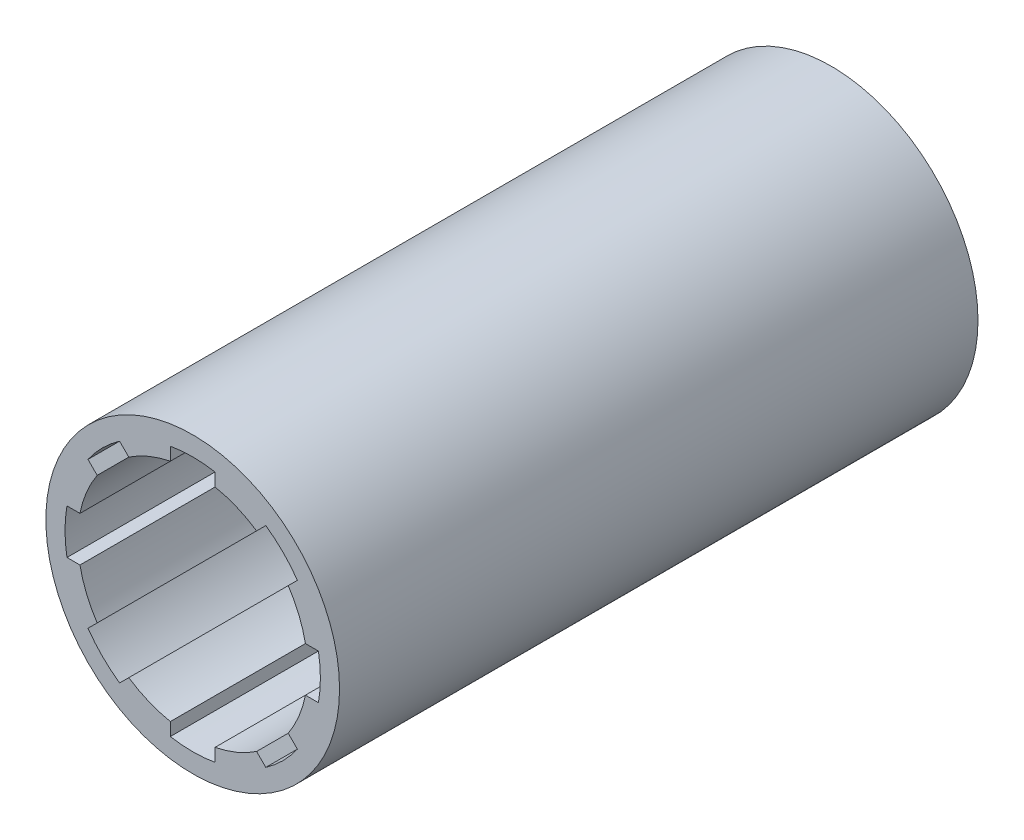
SolidWorks part; units mm, degrees
ref_plane "前视" through (0, 0, 0) normal (0, 0, 1) x (1, 0, 0)
ref_plane "上视" through (0, 0, 0) normal (0, 1, 0) x (1, 0, 0)
ref_plane "右视" through (0, 0, 0) normal (1, 0, 0) x (0, 0, -1)
sketch "草图1" plane through (0, 0, 0) normal (0, 0, 1) x (1, 0, 0)
  circle A0 centre (0, 0) radius 20
  circle A1 centre (0, 0) radius 23
extrude "凸台-拉伸1" add sketch "草图1" along normal blind 100
sketch "草图2" plane through (0, 0, 100) normal (0, 0, 1) x (1, 0, 0)
  line L0 (0, 25.9683) -> (0, -26.9652) construction
  line L1 (28.5193, 0) -> (-30.328, 0) construction
  line L2 (11.449, 16.3988) -> (10.0101, 14.9599)
  line L3 (3.5, 19.6914) -> (3.5, 17.6564)
  line L4 (-3.5, 19.6914) -> (-3.5, 17.6564)
  line L5 (16.3988, 11.449) -> (14.9599, 10.0101)
  line L6 (19.6914, 3.5) -> (17.6564, 3.5)
  line L7 (19.6914, -3.5) -> (17.6564, -3.5)
  line L8 (16.3988, -11.449) -> (14.9599, -10.0101)
  line L9 (11.449, -16.3988) -> (10.0101, -14.9599)
  line L10 (3.5, -19.6914) -> (3.5, -17.6564)
  line L11 (-3.5, -19.6914) -> (-3.5, -17.6564)
  line L12 (-11.449, -16.3988) -> (-10.0101, -14.9599)
  line L13 (-16.3988, -11.449) -> (-14.9599, -10.0101)
  line L14 (-19.6914, -3.5) -> (-17.6564, -3.5)
  line L15 (-19.6914, 3.5) -> (-17.6564, 3.5)
  line L16 (-16.3988, 11.449) -> (-14.9599, 10.0101)
  line L17 (-11.449, 16.3988) -> (-10.0101, 14.9599)
  line L18 (0, 0) -> (3.5, 17.6564) construction
  arc A0 (10.0101, 14.9599) -> (3.5, 17.6564) centre (0, 0) ccw
  arc A1 (10.0101, 14.9599) -> (3.5, 17.6564) centre (0, 0) ccw
  arc A2 (-19.6914, -3.5) -> (-16.3988, -11.449) centre (0, 0) ccw
  arc A3 (-19.6914, -3.5) -> (-16.3988, -11.449) centre (0, 0) ccw
  arc A4 (10.0101, 14.9599) -> (3.5, 17.6564) centre (0, 0) ccw
  arc A5 (-19.6914, -3.5) -> (-16.3988, -11.449) centre (0, 0) ccw
  arc A6 (10.0101, 14.9599) -> (3.5, 17.6564) centre (0, 0) ccw
  arc A7 (-19.6914, -3.5) -> (-16.3988, -11.449) centre (0, 0) ccw
  arc A8 (10.0101, 14.9599) -> (3.5, 17.6564) centre (0, 0) ccw
  arc A9 (-19.6914, -3.5) -> (-16.3988, -11.449) centre (0, 0) ccw
  arc A10 (10.0101, 14.9599) -> (3.5, 17.6564) centre (0, 0) ccw
  arc A11 (-19.6914, -3.5) -> (-16.3988, -11.449) centre (0, 0) ccw
  arc A12 (10.0101, 14.9599) -> (3.5, 17.6564) centre (0, 0) ccw
  arc A13 (-19.6914, -3.5) -> (-16.3988, -11.449) centre (0, 0) ccw
  arc A14 (10.0101, 14.9599) -> (3.5, 17.6564) centre (0, 0) ccw
  arc A15 (-19.6914, -3.5) -> (-16.3988, -11.449) centre (0, 0) ccw
  arc A16 (-3.5, 17.6564) -> (-10.0101, 14.9599) centre (0, 0) ccw
  arc A17 (-3.5, 17.6564) -> (-10.0101, 14.9599) centre (0, 0) ccw
  arc A18 (-3.5, 17.6564) -> (-10.0101, 14.9599) centre (0, 0) ccw
  arc A19 (-3.5, 17.6564) -> (-10.0101, 14.9599) centre (0, 0) ccw
  arc A20 (-3.5, 17.6564) -> (-10.0101, 14.9599) centre (0, 0) ccw
  arc A21 (-3.5, 17.6564) -> (-10.0101, 14.9599) centre (0, 0) ccw
  arc A22 (-3.5, 17.6564) -> (-10.0101, 14.9599) centre (0, 0) ccw
  arc A23 (-3.5, 17.6564) -> (-10.0101, 14.9599) centre (0, 0) ccw
  arc A24 (-14.9599, 10.0101) -> (-17.6564, 3.5) centre (0, 0) ccw
  arc A25 (-14.9599, 10.0101) -> (-17.6564, 3.5) centre (0, 0) ccw
  arc A26 (-14.9599, 10.0101) -> (-17.6564, 3.5) centre (0, 0) ccw
  arc A27 (-14.9599, 10.0101) -> (-17.6564, 3.5) centre (0, 0) ccw
  arc A28 (-14.9599, 10.0101) -> (-17.6564, 3.5) centre (0, 0) ccw
  arc A29 (-14.9599, 10.0101) -> (-17.6564, 3.5) centre (0, 0) ccw
  arc A30 (-14.9599, 10.0101) -> (-17.6564, 3.5) centre (0, 0) ccw
  arc A31 (-14.9599, 10.0101) -> (-17.6564, 3.5) centre (0, 0) ccw
  arc A32 (-17.6564, -3.5) -> (-14.9599, -10.0101) centre (0, 0) ccw
  arc A33 (-17.6564, -3.5) -> (-14.9599, -10.0101) centre (0, 0) ccw
  arc A34 (-17.6564, -3.5) -> (-14.9599, -10.0101) centre (0, 0) ccw
  arc A35 (-17.6564, -3.5) -> (-14.9599, -10.0101) centre (0, 0) ccw
  arc A36 (-17.6564, -3.5) -> (-14.9599, -10.0101) centre (0, 0) ccw
  arc A37 (-17.6564, -3.5) -> (-14.9599, -10.0101) centre (0, 0) ccw
  arc A38 (-17.6564, -3.5) -> (-14.9599, -10.0101) centre (0, 0) ccw
  arc A39 (-17.6564, -3.5) -> (-14.9599, -10.0101) centre (0, 0) ccw
  arc A40 (-10.0101, -14.9599) -> (-3.5, -17.6564) centre (0, 0) ccw
  arc A41 (-10.0101, -14.9599) -> (-3.5, -17.6564) centre (0, 0) ccw
  arc A42 (-10.0101, -14.9599) -> (-3.5, -17.6564) centre (0, 0) ccw
  arc A43 (-10.0101, -14.9599) -> (-3.5, -17.6564) centre (0, 0) ccw
  arc A44 (-10.0101, -14.9599) -> (-3.5, -17.6564) centre (0, 0) ccw
  arc A45 (-10.0101, -14.9599) -> (-3.5, -17.6564) centre (0, 0) ccw
  arc A46 (-10.0101, -14.9599) -> (-3.5, -17.6564) centre (0, 0) ccw
  arc A47 (-10.0101, -14.9599) -> (-3.5, -17.6564) centre (0, 0) ccw
  arc A48 (3.5, -17.6564) -> (10.0101, -14.9599) centre (0, 0) ccw
  arc A49 (3.5, -17.6564) -> (10.0101, -14.9599) centre (0, 0) ccw
  arc A50 (3.5, -17.6564) -> (10.0101, -14.9599) centre (0, 0) ccw
  arc A51 (3.5, -17.6564) -> (10.0101, -14.9599) centre (0, 0) ccw
  arc A52 (3.5, -17.6564) -> (10.0101, -14.9599) centre (0, 0) ccw
  arc A53 (3.5, -17.6564) -> (10.0101, -14.9599) centre (0, 0) ccw
  arc A54 (3.5, -17.6564) -> (10.0101, -14.9599) centre (0, 0) ccw
  arc A55 (3.5, -17.6564) -> (10.0101, -14.9599) centre (0, 0) ccw
  arc A56 (14.9599, -10.0101) -> (17.6564, -3.5) centre (0, 0) ccw
  arc A57 (14.9599, -10.0101) -> (17.6564, -3.5) centre (0, 0) ccw
  arc A58 (14.9599, -10.0101) -> (17.6564, -3.5) centre (0, 0) ccw
  arc A59 (14.9599, -10.0101) -> (17.6564, -3.5) centre (0, 0) ccw
  arc A60 (14.9599, -10.0101) -> (17.6564, -3.5) centre (0, 0) ccw
  arc A61 (14.9599, -10.0101) -> (17.6564, -3.5) centre (0, 0) ccw
  arc A62 (14.9599, -10.0101) -> (17.6564, -3.5) centre (0, 0) ccw
  arc A63 (14.9599, -10.0101) -> (17.6564, -3.5) centre (0, 0) ccw
  arc A64 (17.6564, 3.5) -> (14.9599, 10.0101) centre (0, 0) ccw
  arc A65 (17.6564, 3.5) -> (14.9599, 10.0101) centre (0, 0) ccw
  arc A66 (17.6564, 3.5) -> (14.9599, 10.0101) centre (0, 0) ccw
  arc A67 (17.6564, 3.5) -> (14.9599, 10.0101) centre (0, 0) ccw
  arc A68 (17.6564, 3.5) -> (14.9599, 10.0101) centre (0, 0) ccw
  arc A69 (17.6564, 3.5) -> (14.9599, 10.0101) centre (0, 0) ccw
  arc A70 (17.6564, 3.5) -> (14.9599, 10.0101) centre (0, 0) ccw
  arc A71 (17.6564, 3.5) -> (14.9599, 10.0101) centre (0, 0) ccw
  arc A72 (-11.449, -16.3988) -> (-3.5, -19.6914) centre (0, 0) ccw
  arc A73 (-11.449, -16.3988) -> (-3.5, -19.6914) centre (0, 0) ccw
  arc A74 (-11.449, -16.3988) -> (-3.5, -19.6914) centre (0, 0) ccw
  arc A75 (-11.449, -16.3988) -> (-3.5, -19.6914) centre (0, 0) ccw
  arc A76 (-11.449, -16.3988) -> (-3.5, -19.6914) centre (0, 0) ccw
  arc A77 (-11.449, -16.3988) -> (-3.5, -19.6914) centre (0, 0) ccw
  arc A78 (-11.449, -16.3988) -> (-3.5, -19.6914) centre (0, 0) ccw
  arc A79 (-11.449, -16.3988) -> (-3.5, -19.6914) centre (0, 0) ccw
  arc A80 (3.5, -19.6914) -> (11.449, -16.3988) centre (0, 0) ccw
  arc A81 (3.5, -19.6914) -> (11.449, -16.3988) centre (0, 0) ccw
  arc A82 (3.5, -19.6914) -> (11.449, -16.3988) centre (0, 0) ccw
  arc A83 (3.5, -19.6914) -> (11.449, -16.3988) centre (0, 0) ccw
  arc A84 (3.5, -19.6914) -> (11.449, -16.3988) centre (0, 0) ccw
  arc A85 (3.5, -19.6914) -> (11.449, -16.3988) centre (0, 0) ccw
  arc A86 (3.5, -19.6914) -> (11.449, -16.3988) centre (0, 0) ccw
  arc A87 (3.5, -19.6914) -> (11.449, -16.3988) centre (0, 0) ccw
  arc A88 (16.3988, -11.449) -> (19.6914, -3.5) centre (0, 0) ccw
  arc A89 (16.3988, -11.449) -> (19.6914, -3.5) centre (0, 0) ccw
  arc A90 (16.3988, -11.449) -> (19.6914, -3.5) centre (0, 0) ccw
  arc A91 (16.3988, -11.449) -> (19.6914, -3.5) centre (0, 0) ccw
  arc A92 (16.3988, -11.449) -> (19.6914, -3.5) centre (0, 0) ccw
  arc A93 (16.3988, -11.449) -> (19.6914, -3.5) centre (0, 0) ccw
  arc A94 (16.3988, -11.449) -> (19.6914, -3.5) centre (0, 0) ccw
  arc A95 (16.3988, -11.449) -> (19.6914, -3.5) centre (0, 0) ccw
  arc A96 (19.6914, 3.5) -> (16.3988, 11.449) centre (0, 0) ccw
  arc A97 (19.6914, 3.5) -> (16.3988, 11.449) centre (0, 0) ccw
  arc A98 (19.6914, 3.5) -> (16.3988, 11.449) centre (0, 0) ccw
  arc A99 (19.6914, 3.5) -> (16.3988, 11.449) centre (0, 0) ccw
  arc A100 (19.6914, 3.5) -> (16.3988, 11.449) centre (0, 0) ccw
  arc A101 (19.6914, 3.5) -> (16.3988, 11.449) centre (0, 0) ccw
  arc A102 (19.6914, 3.5) -> (16.3988, 11.449) centre (0, 0) ccw
  arc A103 (19.6914, 3.5) -> (16.3988, 11.449) centre (0, 0) ccw
  arc A104 (11.449, 16.3988) -> (3.5, 19.6914) centre (0, 0) ccw
  arc A105 (11.449, 16.3988) -> (3.5, 19.6914) centre (0, 0) ccw
  arc A106 (11.449, 16.3988) -> (3.5, 19.6914) centre (0, 0) ccw
  arc A107 (11.449, 16.3988) -> (3.5, 19.6914) centre (0, 0) ccw
  arc A108 (11.449, 16.3988) -> (3.5, 19.6914) centre (0, 0) ccw
  arc A109 (11.449, 16.3988) -> (3.5, 19.6914) centre (0, 0) ccw
  arc A110 (11.449, 16.3988) -> (3.5, 19.6914) centre (0, 0) ccw
  arc A111 (11.449, 16.3988) -> (3.5, 19.6914) centre (0, 0) ccw
  arc A112 (-3.5, 19.6914) -> (-11.449, 16.3988) centre (0, 0) ccw
  arc A113 (-3.5, 19.6914) -> (-11.449, 16.3988) centre (0, 0) ccw
  arc A114 (-3.5, 19.6914) -> (-11.449, 16.3988) centre (0, 0) ccw
  arc A115 (-3.5, 19.6914) -> (-11.449, 16.3988) centre (0, 0) ccw
  arc A116 (-3.5, 19.6914) -> (-11.449, 16.3988) centre (0, 0) ccw
  arc A117 (-3.5, 19.6914) -> (-11.449, 16.3988) centre (0, 0) ccw
  arc A118 (-3.5, 19.6914) -> (-11.449, 16.3988) centre (0, 0) ccw
  arc A119 (-3.5, 19.6914) -> (-11.449, 16.3988) centre (0, 0) ccw
  arc A120 (-16.3988, 11.449) -> (-19.6914, 3.5) centre (0, 0) ccw
  arc A121 (-16.3988, 11.449) -> (-19.6914, 3.5) centre (0, 0) ccw
  arc A122 (-16.3988, 11.449) -> (-19.6914, 3.5) centre (0, 0) ccw
  arc A123 (-16.3988, 11.449) -> (-19.6914, 3.5) centre (0, 0) ccw
  arc A124 (-16.3988, 11.449) -> (-19.6914, 3.5) centre (0, 0) ccw
  arc A125 (-16.3988, 11.449) -> (-19.6914, 3.5) centre (0, 0) ccw
  arc A126 (-16.3988, 11.449) -> (-19.6914, 3.5) centre (0, 0) ccw
  arc A127 (-16.3988, 11.449) -> (-19.6914, 3.5) centre (0, 0) ccw
  point P11 (0, 20)
  circle M2 centre (0, 0) radius 20
  dimension "D1" = 8
  dimension "D2" = 18
extrude "凸台-拉伸2" add sketch "草图2" against normal blind 100 contours A24 L16 L15 M2 | A16 L4 L17 M2 | A0 L2 L3 M2 | A64 L6 L5 M2 | A56 L8 L7 M2 | A48 L10 L9 M2 | A40 L12 L11 M2 | A32 L14 L13 M2
